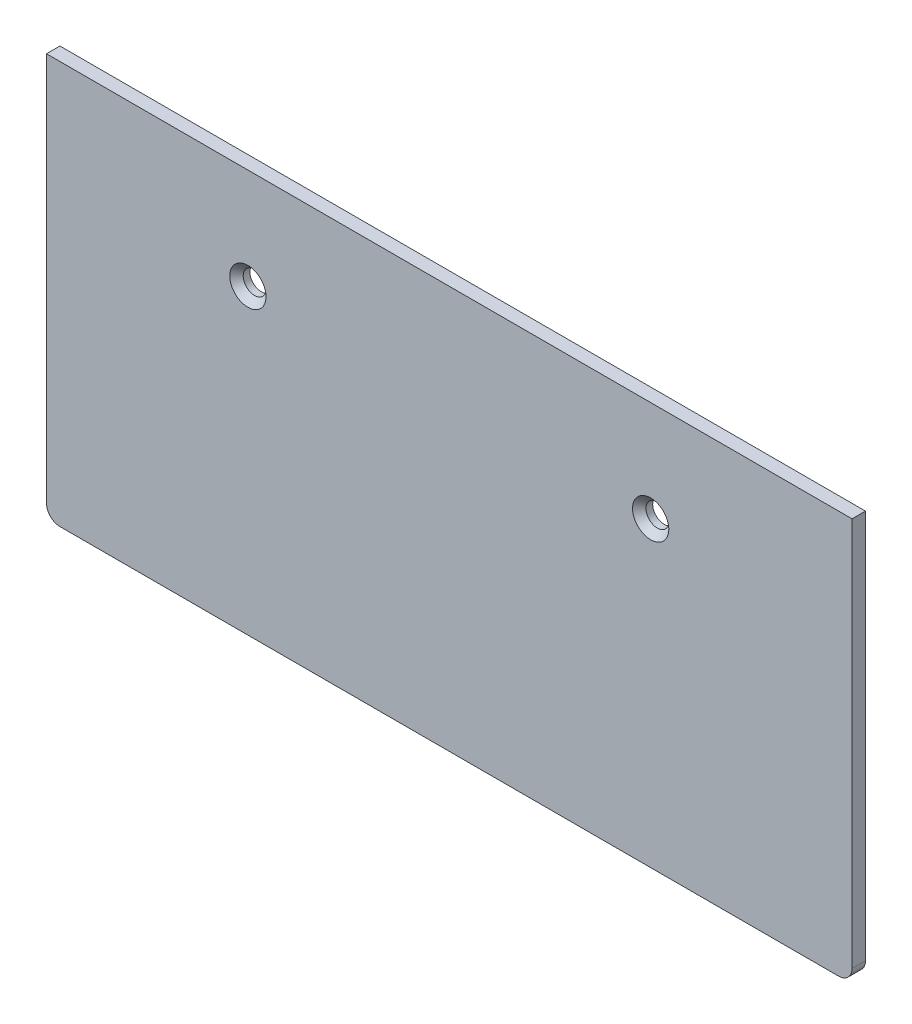
SolidWorks part; units mm, degrees
ref_plane "Piano frontale" through (0, 0, 0) normal (0, 0, 1) x (1, 0, 0)
ref_plane "Piano superiore" through (0, 0, 0) normal (0, 1, 0) x (1, 0, 0)
ref_plane "Piano destro" through (0, 0, 0) normal (1, 0, 0) x (0, 0, -1)
sketch "Schizzo1" plane through (0, 0, 0) normal (0, 0, 1) x (1, 0, 0)
  line L0 (60, 60) -> (60, 0) construction
  line L1 (0, 0) -> (120, 0)
  line L2 (0, 0) -> (0, 60)
  line L3 (0, 60) -> (120, 60)
  line L4 (120, 0) -> (120, 60)
  circle A0 centre (90, 45) radius 1.7
  circle A1 centre (30, 45) radius 1.7
  dimension "D5" = 3.4
  dimension "D1" = 60
  dimension "D2" = 120
  dimension "D3" = 30
  dimension "D4" = 15
extrude "Estrusione-Estrusione2" add sketch "Schizzo1" against normal blind 2
fillet "Raccordo1" radius 2 1 edges at (0, 0, -1)
fillet "Raccordo2" radius 2 1 edges at (120, 0, -1)
chamfer "Smusso1" distance 1 angle 45 1 edges at (28.3, 45, 0)
chamfer "Smusso2" distance 1 angle 45 1 edges at (91.7, 45, 0)
